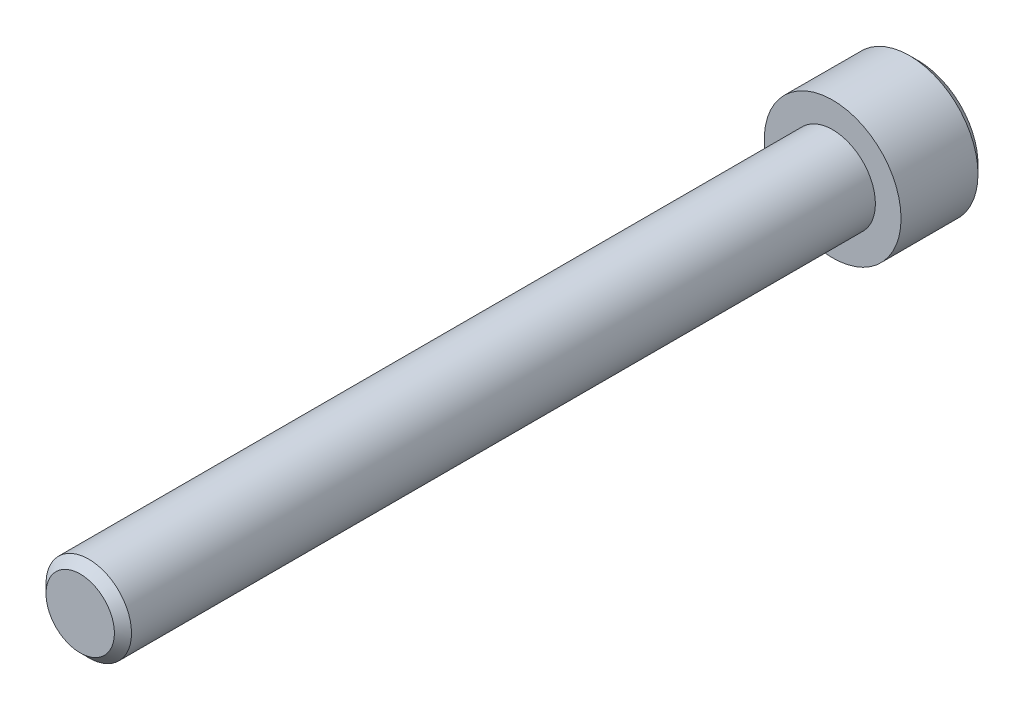
SolidWorks part; units mm, degrees
ref_plane "前视基准面" through (0, 0, 0) normal (0, 0, 1) x (1, 0, 0)
ref_plane "上视基准面" through (0, 0, 0) normal (0, 1, 0) x (1, 0, 0)
ref_plane "右视基准面" through (0, 0, 0) normal (1, 0, 0) x (0, 0, -1)
sketch "草图1" plane through (0, 0, 0) normal (0, 1, 0) x (1, 0, 0)
  line L0 (8, 0) -> (0, 0)
  line L1 (0, 0) -> (0, -10)
  line L2 (0, -10) -> (8, -10)
  line L3 (8, -10) -> (8, 0)
  line L4 (0, 0) -> (0, -10) construction
revolve "旋转1" add sketch "草图1" angle 360 about L4
sketch "草图2" plane through (0, 0, 10) normal (0, 0, 1) x (1, 0, 0)
  circle A0 centre (0, 0) radius 5
extrude "凸台-拉伸1" add sketch "草图2" along normal blind 88
sketch "草图3" plane through (0, 0, 0) normal (0, 0, -1) x (-1, 0, 0)
  line L0 (-2.3094, 4) -> (-4.6188, 0)
  line L1 (-4.6188, 0) -> (-2.3094, -4)
  line L2 (-2.3094, -4) -> (2.3094, -4)
  line L3 (2.3094, -4) -> (4.6188, 0)
  line L4 (4.6188, 0) -> (2.3094, 4)
  line L5 (2.3094, 4) -> (-2.3094, 4)
extrude "切除-拉伸1" cut sketch "草图3" against normal blind 7
chamfer "倒角1" distance 1 angle 45 2 edges at (5, 0, 98) (8, 0, 0)
